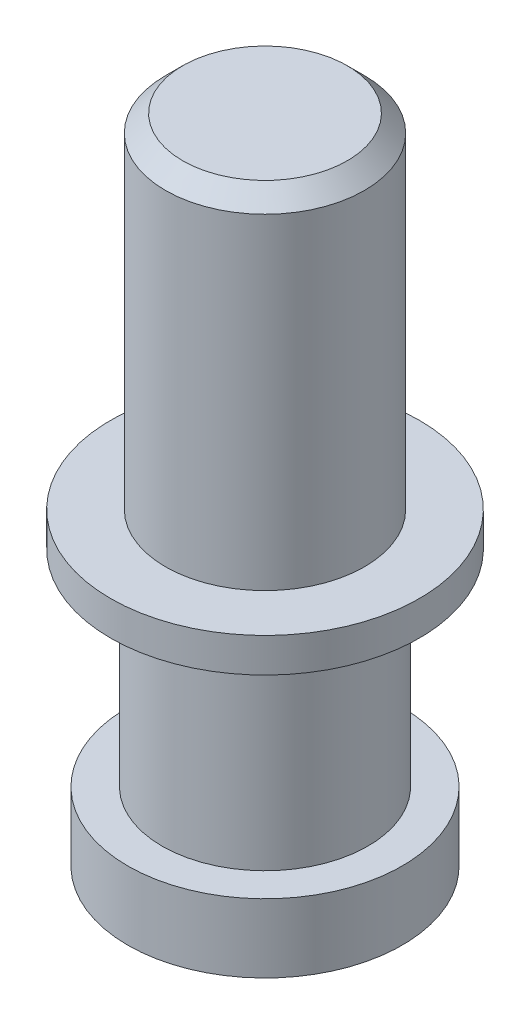
SolidWorks part; units mm, degrees
ref_plane "Front Plane" through (0, 0, 0) normal (0, 0, 1) x (1, 0, 0)
ref_plane "Top Plane" through (0, 0, 0) normal (0, 1, 0) x (1, 0, 0)
ref_plane "Right Plane" through (0, 0, 0) normal (1, 0, 0) x (0, 0, -1)
sketch "Sketch2" plane through (0, 0, 0) normal (0, 1, 0) x (1, 0, 0)
  circle A0 centre (0, 0) radius 2
  dimension "D1" = 4
extrude "Boss-Extrude1" add sketch "Sketch2" along normal blind 1
sketch "Sketch3" plane through (0, 1, 0) normal (0, 1, 0) x (1, 0, 0)
  circle A0 centre (0, 0) radius 1.5
extrude "Boss-Extrude2" add sketch "Sketch3" along normal blind 3
sketch "Sketch4" plane through (0, 4, 0) normal (0, 1, 0) x (1, 0, 0)
  circle A0 centre (0, 0) radius 2.25
  dimension "D1" = 4.5
extrude "Boss-Extrude3" add sketch "Sketch4" along normal blind 0.5
sketch "Sketch5" plane through (0, 4.5, 0) normal (0, 1, 0) x (1, 0, 0)
  circle A0 centre (0, 0) radius 1.45
  dimension "D1" = 2.9
extrude "Boss-Extrude4" add sketch "Sketch5" along normal blind 5
chamfer "Chamfer3" distance 0.25 angle 45 1 edges at (0, 9.5, 1.45)
